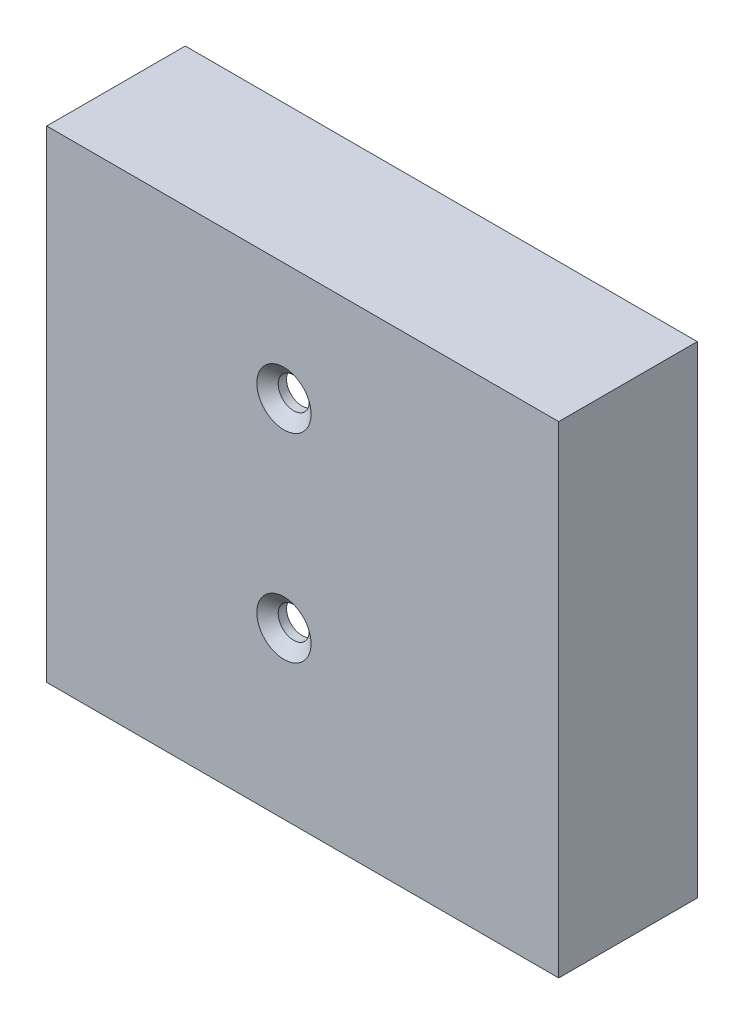
SolidWorks part; units mm, degrees
material "PET"
ref_plane "Front Plane" through (0, 0, 0) normal (0, 0, 1) x (1, 0, 0)
ref_plane "Top Plane" through (0, 0, 0) normal (0, 1, 0) x (1, 0, 0)
ref_plane "Right Plane" through (0, 0, 0) normal (1, 0, 0) x (0, 0, -1)
sketch "Sketch1" plane through (0, 0, 0) normal (0, 0, 1) x (1, 0, 0)
  line L1 (0, 0) -> (52.3875, 0)
  line L2 (0, 0) -> (0, 50.8)
  line L3 (0, 50.8) -> (52.3875, 50.8)
  line L4 (52.3875, 0) -> (52.3875, 50.8)
  dimension "D1" = 50.8
  dimension "D2" = 52.3875
extrude "Boss-Extrude1" add sketch "Sketch1" along normal blind 1.905
sketch "Sketch2" plane through (0, 0, 0) normal (-1, 0, 0) x (0, 0, 1)
  line L1 (1.905, 0) -> (-12.7, 0)
  line L2 (1.905, 0) -> (1.905, 50.8)
  line L3 (1.905, 50.8) -> (-12.7, 50.8)
  line L4 (-12.7, 0) -> (-12.7, 50.8)
  point P6 (1.905, 50.8)
  dimension "D1" = 14.605
extrude "Boss-Extrude2" add sketch "Sketch2" along normal blind 1.5875 contours L3 L4 L1 L2
sketch "Sketch3" plane through (0, 0, 0) normal (0, 0, -1) x (-1, 0, 0)
  line L0 (0, 50.8) -> (-52.3875, 50.8)
  line L1 (-52.3875, 50.8) -> (-52.3875, 0)
  line L2 (-52.3875, 0) -> (0, 0)
  line L3 (0, 0) -> (0, 2.54)
  line L4 (0, 50.8) -> (0, 0) construction
  line L5 (0, 2.54) -> (-49.8475, 2.54)
  line L6 (-49.8475, 2.54) -> (-49.8475, 48.26)
  line L7 (-49.8475, 48.26) -> (0, 48.26)
  line L8 (0, 48.26) -> (0, 50.8)
  dimension "D1" = 2.54
  dimension "D2" = 2.54
  dimension "D3" = 2.54
extrude "Boss-Extrude3" add sketch "Sketch3" along normal up to surface (12.7 mm away) up to face at (-0.7937, 25.4, -12.7)
sketch "Sketch4" plane through (0, 0, 0) normal (0, -1, 0) x (1, 0, 0)
  line L0 (17.145, 0) -> (17.145, -15.24) construction
  line L1 (6.985, -12.7) -> (17.145, -12.7)
  line L2 (6.985, -12.7) -> (6.985, -8.8392)
  line L3 (6.985, -8.8392) -> (17.145, -8.8392)
  line L4 (17.145, -12.7) -> (17.145, -8.8392)
  line L5 (-1.5875, -12.7) -> (52.3875, -12.7) construction
  dimension "D1" = 3.8608
extrude "Cut-Extrude1" cut sketch "Sketch4" against normal up to next contours L3 L4 L1 L2
sketch "Sketch5" plane through (0, 0, 0) normal (0, -1, 0) x (1, 0, 0)
  line L0 (0, 0) -> (49.8475, 0) construction
  line L1 (6.985, -12.7) -> (0, -12.7)
  line L2 (6.985, -12.7) -> (6.985, 0)
  line L3 (6.985, 0) -> (0, 0)
  line L4 (0, -12.7) -> (0, 0)
  line L5 (17.145, -12.7) -> (24.257, -12.7)
  line L6 (17.145, -12.7) -> (17.145, 0)
  line L7 (17.145, 0) -> (24.257, 0)
  line L8 (24.257, -12.7) -> (24.257, 0)
  point P10 (21.3179, 0.3933)
  point P11 (6.985, -0.5096)
  point P12 (0, 0)
  point P13 (24.257, 0)
  point P16 (6.985, 0)
  dimension "D1" = 7.112
  dimension "D2" = 6.985
extrude "Cut-Extrude2" cut sketch "Sketch5" against normal up to next
sketch "Sketch6" plane through (0, 0, 0) normal (0, 0, -1) x (-1, 0, 0)
  line L1 (-17.145, 2.54) -> (-6.985, 2.54)
  line L2 (-17.145, 2.54) -> (-17.145, 5.08)
  line L3 (-17.145, 5.08) -> (-6.985, 5.08)
  line L4 (-6.985, 2.54) -> (-6.985, 5.08)
  point P5 (-6.985, 2.54)
  dimension "D1" = 2.54
extrude "Boss-Extrude4" add sketch "Sketch6" along normal up to surface (8.8392 mm away) up to face at (12.065, 1.27, -8.8392)
sketch "Sketch8" plane through (0, 0, 0) normal (0, 0, -1) x (-1, 0, 0)
  line L1 (0, 48.26) -> (-1.27, 48.26)
  line L2 (0, 48.26) -> (0, 6.858)
  line L3 (0, 6.858) -> (-1.27, 6.858)
  line L4 (-1.27, 48.26) -> (-1.27, 6.858)
  line L5 (-6.985, 0) -> (0, 0) construction
  point P5 (-1.27, 4.9273)
  dimension "D1" = 1.27
  dimension "D2" = 6.858
extrude "Boss-Extrude5" add sketch "Sketch8" along normal offset from surface (14.2875 mm away) 1.5875 contours L4 L3 L2 L1 up to face at (24.9809, 20.32, -12.7) offset beyond the face yes
sketch "Sketch9" plane through (0, 0, -12.7) normal (0, 0, -1) x (-1, 0, 0)
  line L0 (0, 48.26) -> (0, 48.895)
  line L1 (0, 48.895) -> (-50.4825, 48.895)
  line L2 (-50.4825, 48.895) -> (-50.4825, 1.905)
  line L3 (-50.4825, 1.905) -> (-24.257, 1.905)
  line L4 (-24.257, 2.54) -> (-24.257, 0) construction
  line L5 (-24.257, 1.905) -> (-24.257, 2.54)
  line L6 (-24.257, 2.54) -> (-49.8475, 2.54)
  line L7 (-49.8475, 2.54) -> (-49.8475, 48.26)
  line L8 (-49.8475, 48.26) -> (0, 48.26)
  line L9 (1.5875, 50.8) -> (-52.3875, 50.8) construction
  line L10 (-52.3875, 50.8) -> (-52.3875, 0) construction
  line L11 (-24.257, 0) -> (-52.3875, 0) construction
  dimension "D1" = 1.905
  dimension "D2" = 1.905
  dimension "D3" = 1.905
extrude "Boss-Extrude6" add sketch "Sketch9" along normal up to surface (1.5875 mm away) up to face at (0.635, 27.559, -14.2875)
sketch "Sketch11" plane through (1.27, 0, 0) normal (1, 0, 0) x (0, 0, -1)
  line L0 (12.7, 48.895) -> (12.7, 1.905) construction
  line L1 (14.2875, 27.94) -> (12.7, 27.94)
  line L2 (14.2875, 27.94) -> (14.2875, 22.86)
  line L3 (14.2875, 22.86) -> (12.7, 22.86)
  line L4 (12.7, 27.94) -> (12.7, 22.86)
  line L5 (12.7, 14.605) -> (14.2875, 14.605)
  line L6 (12.7, 14.605) -> (12.7, 9.525)
  line L7 (12.7, 9.525) -> (14.2875, 9.525)
  line L8 (14.2875, 14.605) -> (14.2875, 9.525)
  line L9 (14.2875, 48.895) -> (14.2875, 1.905) construction
  line L10 (14.2875, 1.905) -> (12.7, 1.905) construction
  line L11 (12.7, 48.895) -> (14.2875, 48.895)
  line L12 (12.7, 48.895) -> (12.7, 43.815)
  line L13 (12.7, 43.815) -> (14.2875, 43.815)
  line L14 (14.2875, 48.895) -> (14.2875, 43.815)
  line L15 (14.2875, 48.26) -> (14.2875, 6.858) construction
  line L16 (14.2875, 48.895) -> (14.2875, 6.858) construction
  line L17 (-1.905, 50.8) -> (12.7, 50.8) construction
  point P19 (14.2875, 34.1572)
  point P22 (14.2875, 21.2773)
  point P25 (14.2875, 22.8428)
  point P28 (12.8715, 22.86)
  point P29 (12.7, 22.86)
  dimension "D1" = 5.08
  dimension "D2" = 5.08
  dimension "D3" = 5.08
  dimension "D4" = 7.62
  dimension "D5" = 22.86
extrude "Cut-Extrude3" cut sketch "Sketch11" against normal up to next
sketch "Sketch12" plane through (0, 0, 1.905) normal (0, 0, 1) x (1, 0, 0)
  point P0 (23.4188, 17.4625)
  point P1 (23.4188, 38.4175)
hole_wizard "CSK for #4 Flat Head Machine Screw (100)1" positions "Sketch15" profile "Sketch16" countersink size "#4" standard "ANSI Inch"
sketch "Sketch15" plane through (0, 0, 1.905) normal (0, 0, 1) x (1, 0, 0)
  point P0 (23.4188, 38.4175)
  point P3 (23.4188, 17.4625)
sketch "Sketch16" plane through (23.4188, 38.4175, 1.905) normal (1, 0, 0) x (0, -1, 0)
  line L0 (0, 0) -> (0, 8.4736)
  line L1 (0, 8.4736) -> (1.6319, 7.493)
  line L2 (1.6319, 7.493) -> (1.6319, 1.0284)
  line L3 (1.6319, 1.0284) -> (2.8575, 0)
  line L5 (2.8575, 0) -> (0, 0)
  line L6 (-1.6319, 1.0284) -> (-2.8575, 0) construction
  line L10 (0, 8.4736) -> (-1.632, 7.493) construction
  line L11 (0, -6.35) -> (0, 107.95) construction
  dimension "Hole Dia." = 3.2639
  dimension "Hole Depth" = 7.493
  dimension "Near C'Sink Dia." = 5.715
  dimension "Near C'Sink Angle" = 100
  dimension "Drill Angle" = 118
